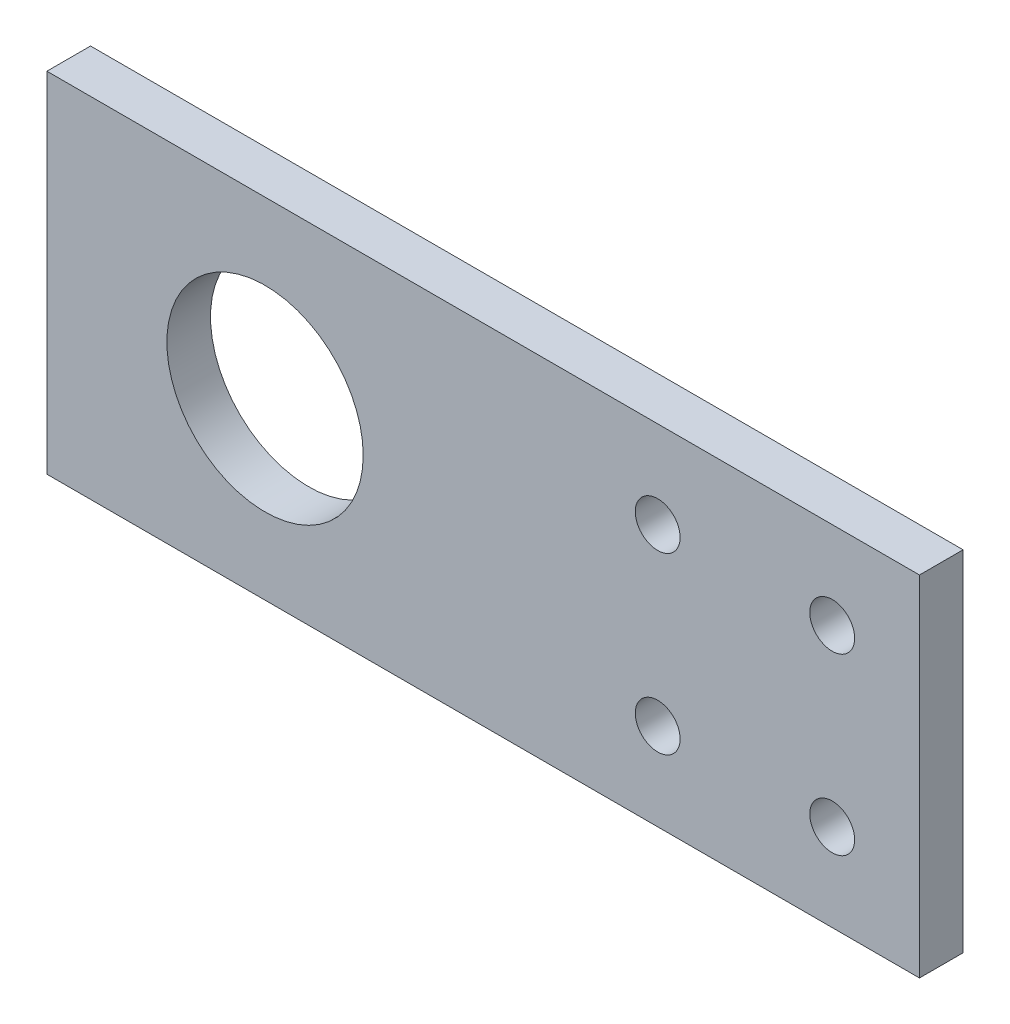
SolidWorks part; units mm, degrees
material "6061 Alloy"
ref_plane "Front Plane" through (0, 0, 0) normal (0, 0, 1) x (1, 0, 0)
ref_plane "Top Plane" through (0, 0, 0) normal (0, 1, 0) x (1, 0, 0)
ref_plane "Right Plane" through (0, 0, 0) normal (1, 0, 0) x (0, 0, -1)
sketch "Sketch1" plane through (0, 0, 0) normal (0, 0, 1) x (1, 0, 0)
  line L0 (0, 0) -> (0, 50.8)
  line L3 (88.9, 12.7) -> (114.3, 12.7) construction
  line L4 (127, 50.8) -> (0, 50.8)
  line L5 (127, 0) -> (0, 0)
  line L7 (127, 50.8) -> (127, 0)
  line L9 (85.6361, 38.1) -> (88.9, 38.1) construction
  line L10 (88.9, 38.1) -> (114.3, 38.1) construction
  line L12 (88.9, 12.7) -> (88.9, 38.1) construction
  line L13 (114.3, 12.7) -> (114.3, 38.1) construction
  line L16 (85.6361, 12.7) -> (88.9, 12.7) construction
  circle A2 centre (88.9, 12.7) radius 3.2639
  circle A3 centre (114.3, 12.7) radius 3.2639
  circle A6 centre (88.9, 38.1) radius 3.2639
  circle A7 centre (114.3, 38.1) radius 3.2639
  dimension "D1" = 88.9
  dimension "D2" = 25.4
  dimension "D4" = 6.5278
  dimension "C" = 50.8
  dimension "D3" = 25.4
  dimension "B" = 127
  dimension "D5" = 12.7
extrude "Boss-Extrude1" add sketch "Sketch1" along normal mid plane 6.35
sketch "Sketch2" plane through (0, 0, 3.175) normal (0, 0, 1) x (1, 0, 0)
  circle A0 centre (31.75, 25.4) radius 14.2875
  dimension "D1" = 28.575
  dimension "D2" = 25.4
  dimension "D3" = 31.75
extrude "Cut-Extrude1" cut sketch "Sketch2" against normal through all
